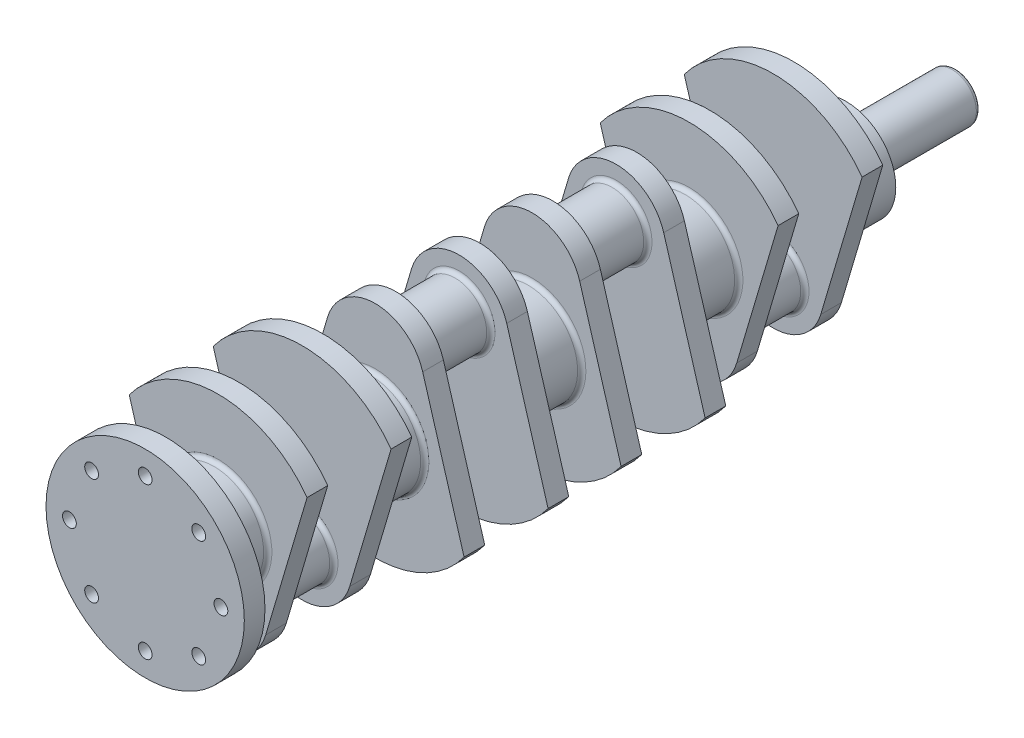
SolidWorks part; units mm, degrees
ref_plane "Front Plane" through (0, 0, 0) normal (0, 0, 1) x (1, 0, 0)
ref_plane "Top Plane" through (0, 0, 0) normal (0, 1, 0) x (1, 0, 0)
ref_plane "Right Plane" through (0, 0, 0) normal (1, 0, 0) x (0, 0, -1)
sketch "Sketch1" plane through (0, 0, 0) normal (0, 0, 1) x (1, 0, 0)
  line L0 (0, 74.4) -> (0, -44) construction
  line L1 (-107.1, 0) -> (112.8, 0) construction
  line L2 (-64.5699, 47.2306) -> (-34.5175, -54.2246)
  line L3 (64.5699, 47.2306) -> (34.5175, -54.2246)
  circle A0 centre (0, -44) radius 36
  arc A1 (-64.5699, 47.2306) -> (64.5699, 47.2306) centre (0, 0) cw
  point P9 (0, 0)
  point P12 (0, 0)
  dimension "D1" = 72
  dimension "D3" = 80
  dimension "D2" = 33
  dimension "D4" = 44
extrude "Boss-Extrude1" add sketch "Sketch1" along normal blind 15 contours A1 L2 A0 L3 | A0
sketch "Sketch2" plane through (0, 0, 15) normal (0, 0, 1) x (1, 0, 0)
  circle A0 centre (0, -44) radius 23
  dimension "D1" = 46
extrude "Boss-Extrude2" add sketch "Sketch2" along normal blind 46
sketch "Sketch3" plane through (0, 0, 0) normal (0, 0, -1) x (-1, 0, 0)
  circle A0 centre (0, 0) radius 36
  dimension "D1" = 72
extrude "Boss-Extrude3" add sketch "Sketch3" along normal blind 38
ref_plane "Plane1" through (0, 0, 38) normal (0, 0, 1) x (1, 0, 0)
mirror "Mirror1" about plane through (0, 0, 38) normal (0, 0, 1) of "Boss-Extrude1", "Boss-Extrude3"
ref_plane "Plane2" through (0, 0, 95) normal (0, 0, 1) x (1, 0, 0)
mirror "Mirror2" about plane through (0, 0, 95) normal (0, 0, 1) of bodies 104
move or copy body "Body-Move/Copy1" bodies to move or copy 105 copy no rotation origin (0, 0, 152) rotation axis (1, 0, 0) rotation angle 180
ref_plane "Plane3" through (0, 0, 209) normal (0, 0, 1) x (1, 0, 0)
mirror "Mirror3" about plane through (0, 0, 209) normal (0, 0, 1) of bodies 106 104
sketch "Sketch4" plane through (0, 0, -38) normal (0, 0, -1) x (-1, 0, 0)
  circle A0 centre (0, 0) radius 17.5
  dimension "D1" = 35
extrude "Boss-Extrude4" add sketch "Sketch4" along normal blind 80
sketch "Sketch5" plane through (0, 0, 456) normal (0, 0, 1) x (1, 0, 0)
  circle A0 centre (0, 0) radius 72
  circle A1 centre (0, 0) radius 55 construction
  circle A2 centre (0, 55) radius 5
  circle A3 centre (0, 0) radius 55 construction
  circle A4 centre (38.8909, 38.8909) radius 5
  circle A5 centre (0, 0) radius 55 construction
  circle A6 centre (55, 0) radius 5
  circle A7 centre (0, 0) radius 55 construction
  circle A8 centre (38.8909, -38.8909) radius 5
  circle A9 centre (0, 0) radius 55 construction
  circle A10 centre (0, -55) radius 5
  circle A11 centre (0, 0) radius 55 construction
  circle A12 centre (-38.8909, -38.8909) radius 5
  circle A13 centre (0, 0) radius 55 construction
  circle A14 centre (-55, 0) radius 5
  circle A15 centre (0, 0) radius 55 construction
  circle A16 centre (-38.8909, 38.8909) radius 5
  dimension "D1" = 144
  dimension "D2" = 110
  dimension "D3" = 10
  dimension "D4" = 8
extrude "Boss-Extrude5" add sketch "Sketch5" along normal blind 15
combine bodies "Combine1" operation type add bodies to combine 109 106 107 110
fillet "Fillet1" radius 3 19 edges at (23, -44, 15) (23, -44, 61) (-36, 0, 0) (-36, 0, 76) (-17.5, 0, -38) (-17.5, 0, -118) (23, 44, 129) (-36, 0, 114) (23, 44, 175) (-36, 0, 190) (23, 44, 289) (-36, 0, 304) (23, 44, 243) (-36, 0, 228) (23, -44, 403) (-36, 0, 418) (23, -44, 357) (-36, 0, 456) (-36, 0, 342)
